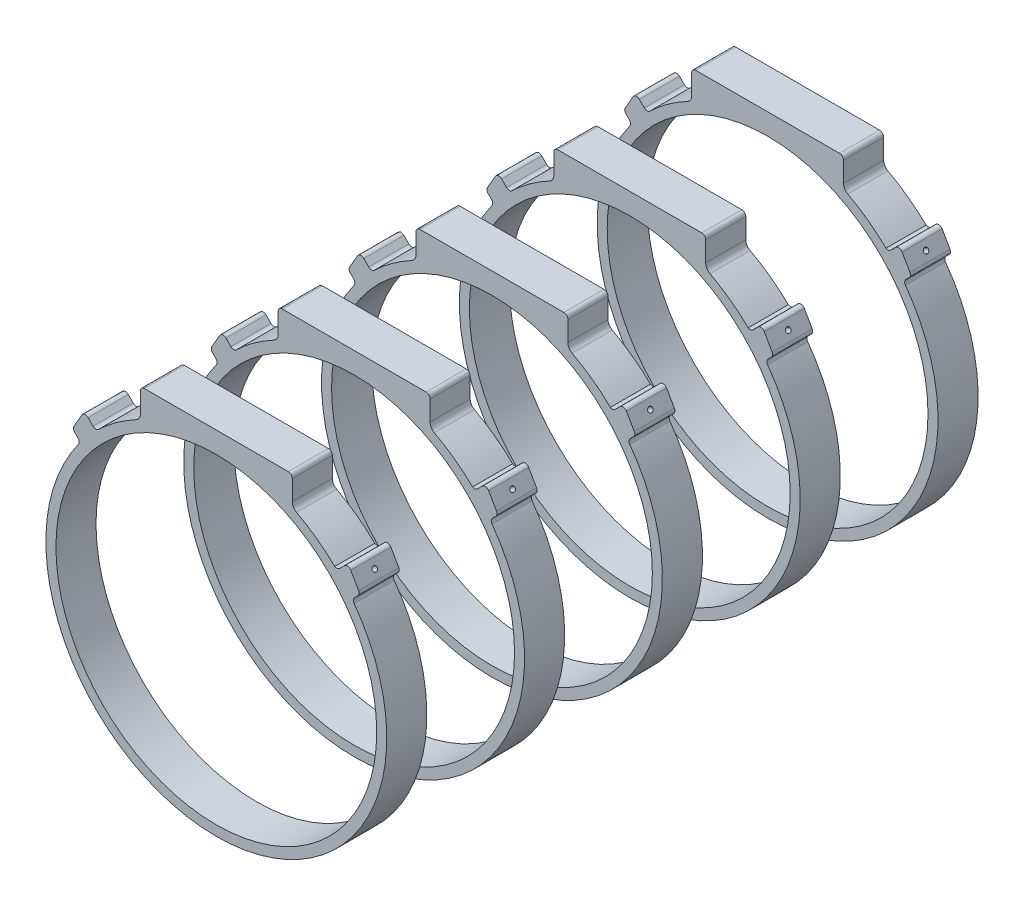
SolidWorks part; units mm, degrees
ref_plane "Front Plane" through (0, 0, 0) normal (0, 0, 1) x (1, 0, 0)
ref_plane "Top Plane" through (0, 0, 0) normal (0, 1, 0) x (1, 0, 0)
ref_plane "Right Plane" through (0, 0, 0) normal (1, 0, 0) x (0, 0, -1)
sketch "Sketch1" plane through (0, 0, 0) normal (0, 0, 1) x (1, 0, 0)
  line L0 (-24.0553, 56.2162) -> (-24.0553, 49.8662)
  line L1 (-22.7853, 57.4862) -> (22.7853, 57.4862)
  line L2 (24.0553, 56.2162) -> (24.0553, 49.8662)
  line L3 (0, 0) -> (-35.921, 35.921) construction
  line L4 (-39.0249, 39.0249) -> (-40.5879, 40.5879)
  line L5 (-43.7889, 33.3798) -> (-44.8791, 34.47)
  line L6 (-45.0809, 36.003) -> (-42.5857, 40.3248)
  line L7 (0, 0) -> (-50.8, 0) construction
  line L8 (0, 0) -> (0, -50.8) construction
  line L12 (0, -50.8) -> (0, 0) construction
  line L16 (-45.5682, 35.1591) -> (-45.2338, 35.1591) construction
  line L17 (39.0249, 39.0249) -> (40.5879, 40.5879)
  line L18 (45.0809, 36.003) -> (42.5857, 40.3248)
  line L19 (43.7889, 33.3798) -> (44.8791, 34.47)
  circle A0 centre (0, 0) radius 50.8
  arc A1 (-25.4, 47.625) -> (-37.5057, 38.8152) centre (0, 0) ccw
  arc A2 (-25.4, 47.625) -> (-24.0553, 49.8662) centre (-26.5953, 49.8662) ccw
  arc A3 (24.0553, 49.8662) -> (25.4, 47.625) centre (26.5953, 49.8662) ccw
  arc A4 (-37.5057, 38.8152) -> (-39.0249, 39.0249) centre (-38.1269, 39.9229) cw
  arc A9 (-43.7889, 33.3798) -> (-43.6598, 31.7352) centre (-44.6871, 32.4819) cw
  arc A10 (-40.5879, 40.5879) -> (-42.5857, 40.3248) centre (-41.4859, 39.6898) ccw
  arc A11 (-44.8791, 34.47) -> (-45.0809, 36.003) centre (-43.9811, 35.368) cw
  arc A12 (37.5057, 38.8152) -> (39.0249, 39.0249) centre (38.1269, 39.9229) ccw
  arc A13 (40.5879, 40.5879) -> (42.5857, 40.3248) centre (41.4859, 39.6898) cw
  arc A14 (44.8791, 34.47) -> (45.0809, 36.003) centre (43.9811, 35.368) ccw
  arc A15 (43.7889, 33.3798) -> (43.6598, 31.7352) centre (44.6871, 32.4819) ccw
  arc A16 (24.0553, 56.2162) -> (22.7853, 57.4862) centre (22.7853, 56.2162) ccw
  arc A17 (-22.7853, 57.4862) -> (-24.0553, 56.2162) centre (-22.7853, 56.2162) ccw
  arc A18 (-53.5379, -6.8552) -> (53.5379, -6.8552) centre (0, 0) ccw
  arc A19 (-43.6598, 31.7352) -> (-53.975, 0) centre (0, 0) ccw
  arc A20 (37.5057, 38.8152) -> (25.4, 47.625) centre (0, 0) ccw
  arc A21 (53.975, 0) -> (43.6598, 31.7352) centre (0, 0) ccw
  arc A22 (-53.5379, -6.8552) -> (-53.975, 0) centre (0, 0) cw
  arc A23 (53.975, 0) -> (53.5379, -6.8552) centre (0, 0) cw
  point P5 (0, 57.4862)
  point P8 (0, 0)
  point P28 (0, 0)
  point P31 (0, 53.473)
  point P33 (0, 39.9229)
  point P34 (0, 37.2882)
  point P39 (0, 0)
  dimension "D1" = 101.6
  dimension "D2" = 107.95
  dimension "D3" = 2.54
  dimension "D4" = 2.54
  dimension "D5" = 6.35
  dimension "D6" = 50.8
  dimension "D12" = 1.27
  dimension "D13" = 1.27
  dimension "D14" = 1.27
  dimension "D16" = 1.27
  dimension "D17" = 1.27
  dimension "D18" = 1.27
  dimension "D20" = 45.0809
  dimension "D7" = 6.8552
  dimension "D8" = 5.08
  dimension "D10" = 45
  dimension "D11" = 60
  dimension "D15" = 1.5418
  dimension "D19" = 2.2103
extrude "Boss-Extrude1" add sketch "Sketch1" along normal blind 12.7
pattern_linear "LPattern2" count 5 spacing 43.6499 along (0, 0, 1) of bodies 101
sketch "Sketch3" plane through (-49.4005, 28.5214, 0) normal (-0.866, 0.5, 0) x (0, 0, 1)
  line L0 (12.7, 13.6295) -> (12.7, 8.6391) construction
  line L1 (12.7, 8.6391) -> (0, 8.6391) construction
  point P0 (6.35, 11.1343)
  point P3 (12.7, 11.1343)
  point P6 (6.35, 8.6391)
  point P7 (0, 0)
hole_wizard "1/16 (0.0625) Diameter Hole1" positions "Sketch5" profile "Sketch7" hole size "1/16" standard "ANSI Inch"
sketch "Sketch5" plane through (-49.4005, 28.5214, 0) normal (-0.866, 0.5, 0) x (0, 0, 1)
  point P0 (6.35, 11.1343)
sketch "Sketch7" plane through (-43.8333, 38.1639, 6.35) normal (0, 0, 1) x (-0.5, -0.866, 0)
  line L0 (0, 0) -> (0, 3.81)
  line L1 (0, 3.81) -> (0.7937, 3.3331)
  line L2 (0.7937, 3.3331) -> (0.7937, 0)
  line L5 (0.7937, 0) -> (0, 0)
  line L10 (0, 3.81) -> (-0.7938, 3.3331) construction
  line L11 (0, -6.35) -> (0, 107.95) construction
  dimension "Hole Dia." = 1.5875
  dimension "Hole Depth" = 3.81
  dimension "Drill Angle" = 118
pattern_linear "LPattern3" count 5 spacing 43.6499 along (0, 0, 1) of "1/16 (0.0625) Diameter Hole1"
sketch "Sketch9" plane through (49.4005, 28.5214, 0) normal (0.866, 0.5, 0) x (0, 0, -1)
  line L0 (0, 8.6391) -> (0, 13.6295) construction
  line L1 (-12.7, 13.6295) -> (0, 13.6295) construction
  point P0 (-6.35, 11.1343)
  point P3 (0, 11.1343)
  point P6 (-6.35, 13.6295)
hole_wizard "1/16 (0.0625) Diameter Hole2" positions "Sketch9" profile "Sketch10" hole size "1/16" standard "ANSI Inch"
sketch "Sketch10" plane through (43.8333, 38.1639, 6.35) normal (0, 0, 1) x (-0.5, 0.866, 0)
  line L0 (0, 0) -> (0, 3.81)
  line L1 (0, 3.81) -> (0.7937, 3.3331)
  line L2 (0.7937, 3.3331) -> (0.7937, 0)
  line L5 (0.7937, 0) -> (0, 0)
  line L10 (0, 3.81) -> (-0.7938, 3.3331) construction
  line L11 (0, -6.35) -> (0, 107.95) construction
  dimension "Hole Dia." = 1.5875
  dimension "Hole Depth" = 3.81
  dimension "Drill Angle" = 118
pattern_linear "LPattern4" count 5 spacing 43.6499 along (0, 0, 1) of "1/16 (0.0625) Diameter Hole2"
